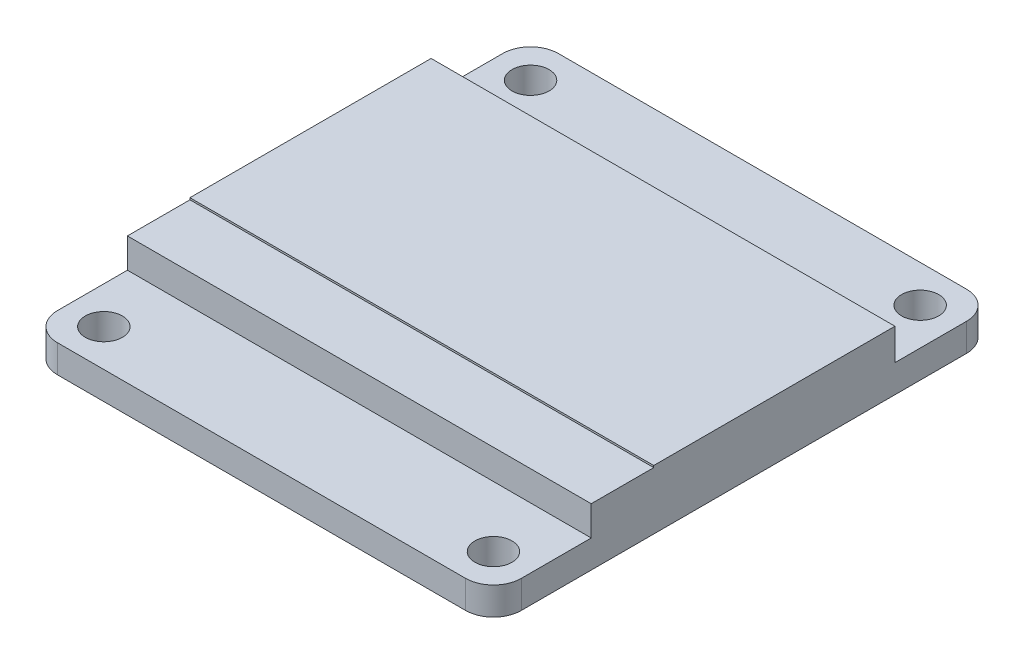
SolidWorks part; units mm, degrees
ref_plane "前视基准面" through (0, 0, 0) normal (0, 0, 1) x (1, 0, 0)
ref_plane "上视基准面" through (0, 0, 0) normal (0, 1, 0) x (1, 0, 0)
ref_plane "右视基准面" through (0, 0, 0) normal (1, 0, 0) x (0, 0, -1)
sketch "草图2" plane through (0, 0, 0) normal (0, 1, 0) x (1, 0, 0)
  line L1 (-118.2575, 92.3321) -> (-96.2575, 92.3321)
  line L2 (-119.7575, 90.8321) -> (-119.7575, 66.8321)
  line L3 (-118.2575, 65.3321) -> (-96.2575, 65.3321)
  line L4 (-94.7575, 90.8321) -> (-94.7575, 66.8321)
  arc A0 (-96.2575, 92.3321) -> (-94.7575, 90.8321) centre (-96.2575, 90.8321) cw
  arc A1 (-96.2575, 65.3321) -> (-94.7575, 66.8321) centre (-96.2575, 66.8321) ccw
  arc A2 (-119.7575, 66.8321) -> (-118.2575, 65.3321) centre (-118.2575, 66.8321) ccw
  arc A3 (-118.2575, 92.3321) -> (-119.7575, 90.8321) centre (-118.2575, 90.8321) ccw
  point P6 (-94.7575, 92.3321)
  point P9 (-94.7575, 65.3321)
  point P14 (-119.7575, 92.3321)
  dimension "D3" = 1.5
  dimension "D4" = 1.5
  dimension "D1" = 25
  dimension "D2" = 27
extrude "凸台-拉伸1" add sketch "草图2" along normal blind 1.5
sketch "草图3" plane through (0, 1.5, 0) normal (0, 1, 0) x (1, 0, 0)
  line L0 (-96.2575, 92.3321) -> (-118.2575, 92.3321) construction
  line L1 (-94.7575, 66.8321) -> (-94.7575, 90.8321) construction
  line L2 (-118.2575, 65.3321) -> (-96.2575, 65.3321) construction
  line L3 (-119.7575, 90.8321) -> (-119.7575, 66.8321) construction
  circle A0 centre (-117.7575, 90.3321) radius 1
  circle A1 centre (-96.7575, 90.3321) radius 1
  circle A2 centre (-96.7575, 67.3321) radius 1
  circle A3 centre (-117.7575, 67.3321) radius 1
  point P10 (0, 0)
  point P17 (0, 0)
  point P18 (0, 0)
  point P19 (0, 0)
  dimension "D5" = 2
  dimension "D1" = 2
  dimension "D2" = 2
  dimension "D3" = 2
  dimension "D4" = 2
extrude "切除-拉伸1" cut sketch "草图3" against normal through all
sketch "草图4" plane through (0, 1.5, 0) normal (0, 1, 0) x (1, 0, 0)
  line L0 (-119.7575, 90.8321) -> (-119.7575, 66.8321) construction
  line L1 (-119.7575, 86.9721) -> (-94.7575, 86.9721)
  line L2 (-119.7575, 86.9721) -> (-119.7575, 70.6021)
  line L3 (-119.7575, 70.6021) -> (-94.7575, 70.6021)
  line L4 (-94.7575, 86.9721) -> (-94.7575, 70.6021)
  line L5 (-94.7575, 66.8321) -> (-94.7575, 90.8321) construction
  line L6 (-96.2575, 92.3321) -> (-118.2575, 92.3321) construction
  dimension "D1" = 5.36
  dimension "D2" = 16.37
extrude "凸台-拉伸2" add sketch "草图4" along normal blind 1.6
sketch "草图5" plane through (0, 3.1, 0) normal (0, 1, 0) x (1, 0, 0)
  line L0 (-94.7575, 70.6021) -> (-94.7575, 86.9721) construction
  line L1 (-119.7575, 86.9721) -> (-94.7575, 86.9721)
  line L2 (-119.7575, 86.9721) -> (-119.7575, 73.9721)
  line L3 (-119.7575, 73.9721) -> (-94.7575, 73.9721)
  line L4 (-94.7575, 86.9721) -> (-94.7575, 73.9721)
  dimension "D1" = 13
extrude "凸台-拉伸3" add sketch "草图5" along normal blind 0.1
